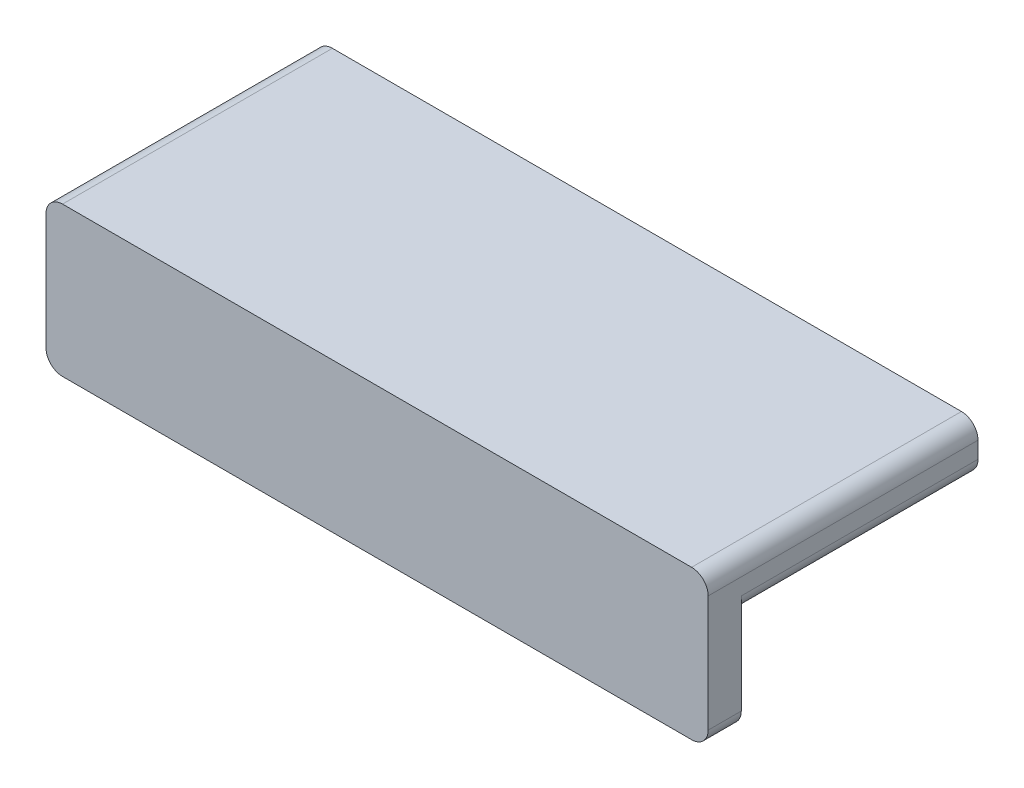
SolidWorks part; units mm, degrees
ref_plane "Front Plane" through (0, 0, 0) normal (0, 0, 1) x (1, 0, 0)
ref_plane "Top Plane" through (0, 0, 0) normal (0, 1, 0) x (1, 0, 0)
ref_plane "Right Plane" through (0, 0, 0) normal (1, 0, 0) x (0, 0, -1)
sketch "Sketch2" plane through (0, 0, 0) normal (0, 0, 1) x (1, 0, 0)
  line L0 (-4.98, -2.255) -> (4.98, -2.255)
  line L1 (4.98, -2.255) -> (4.98, 0.755)
  line L2 (4.98, 0.755) -> (10, 0.755)
  line L3 (10, 0.755) -> (10, 2.255)
  line L4 (10, 2.255) -> (-10, 2.255)
  line L5 (-10, 2.255) -> (-10, 0.755)
  line L6 (-10, 0.755) -> (-4.98, 0.755)
  line L7 (-4.98, 0.755) -> (-4.98, -2.255)
  line L8 (0, 0) -> (0, -14367.8733) construction
  line L10 (-4.98, 2.255) -> (4.98, 2.255) construction
  line L11 (-4.98, 2.255) -> (-4.98, -2.255) construction
  line L12 (-4.98, -2.255) -> (4.98, -2.255) construction
  line L13 (4.98, 2.255) -> (4.98, -2.255) construction
  line L14 (-4.98, 2.255) -> (4.98, -2.255) construction
  line L15 (-4.98, -2.255) -> (4.98, 2.255) construction
  point P11 (0, -2.255)
  point P12 (0, 0)
  dimension "D1" = 9.96
  dimension "D2" = 1.5
  dimension "D3" = 3.01
  dimension "D4" = 20
extrude "Boss-Extrude1" add sketch "Sketch2" along normal mid plane 7.15
sketch "Sketch3" plane through (0, 0, 3.575) normal (0, 0, 1) x (1, 0, 0)
  line L1 (-10, -2.255) -> (10, -2.255)
  line L2 (-10, -2.255) -> (-10, 2.255)
  line L3 (-10, 2.255) -> (10, 2.255)
  line L4 (10, -2.255) -> (10, 2.255)
  line L5 (-10, -2.255) -> (10, 2.255) construction
  line L6 (-10, 2.255) -> (10, -2.255) construction
  point P0 (0, 0)
extrude "Boss-Extrude2" add sketch "Sketch3" along normal blind 1
fillet "Fillet1" radius 0.5 8 edges at (-10, 2.255, 0.5) (10, 2.255, 0.5) (-10, -2.255, 4.075) (-4.98, -2.255, 0) (-10, 0.755, 0) (4.98, -2.255, 0) (10, -2.255, 4.075) (10, 0.755, 0)
equation "\"tolerance\"= 0.2mm"
equation "\"D1@Sketch2\"=10.16 - \"tolerance\""
equation "\"D3@Sketch2\"=3.21 - \"tolerance\""
equation "\"D1@Boss-Extrude1\"=7.35 - \"tolerance\""
